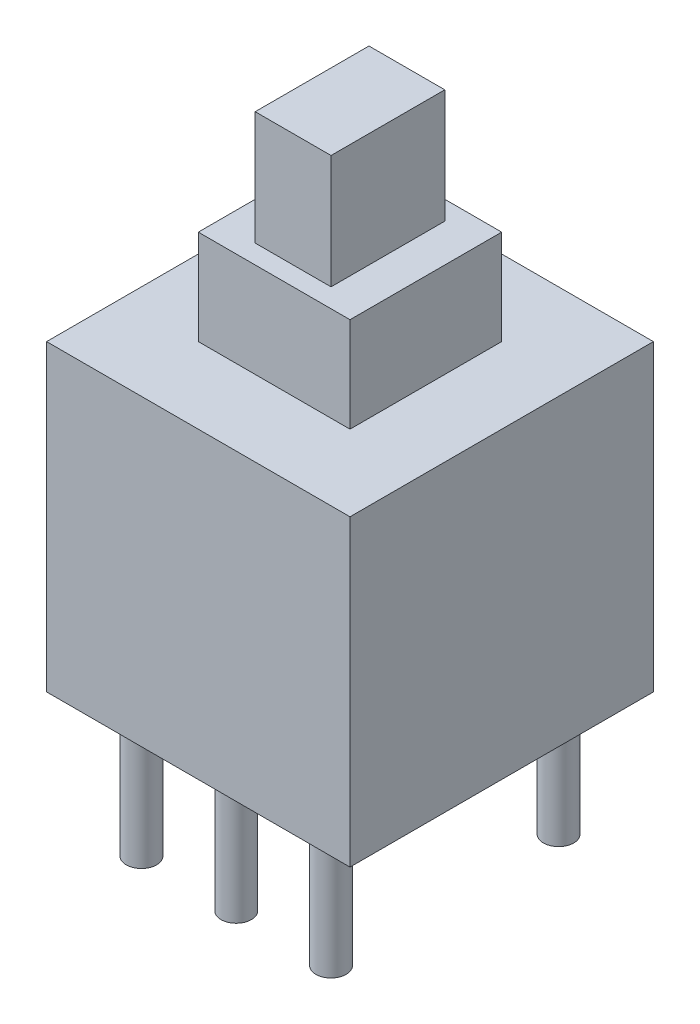
SolidWorks part; units mm, degrees
ref_plane "Front Plane" through (0, 0, 0) normal (0, 0, 1) x (1, 0, 0)
ref_plane "Top Plane" through (0, 0, 0) normal (0, 1, 0) x (1, 0, 0)
ref_plane "Right Plane" through (0, 0, 0) normal (1, 0, 0) x (0, 0, -1)
sketch "Sketch1" plane through (0, 0, 0) normal (0, 1, 0) x (1, 0, 0)
  line L0 (-4, 4) -> (4, -4) construction
  line L1 (-4, 4) -> (4, 4)
  line L2 (-4, 4) -> (-4, -4)
  line L3 (-4, -4) -> (4, -4)
  line L4 (4, 4) -> (4, -4)
  dimension "D1" = 8
extrude "Boss-Extrude1" add sketch "Sketch1" along normal blind 8
sketch "Sketch2" plane through (0, 8, 0) normal (0, 1, 0) x (1, 0, 0)
  line L5 (-2, -2) -> (2, -2)
  line L6 (-2, -2) -> (-2, 2)
  line L7 (-2, 2) -> (2, 2)
  line L8 (2, -2) -> (2, 2)
  line L9 (-2, -2) -> (2, 2) construction
  line L10 (-2, 2) -> (2, -2) construction
  point P4 (0, 0)
  dimension "D1" = 4
extrude "Boss-Extrude2" add sketch "Sketch2" along normal blind 5.5
sketch "Sketch3" plane through (0, 0, 0) normal (0, -1, 0) x (1, 0, 0)
  line L0 (0, -4.4) -> (0, 4.4) construction
  line L1 (-1.8601, 0) -> (1.942, 0) construction
  line L2 (4.4, 0) -> (-4.4, 0) construction
  line L3 (0, 3) -> (-2.5, 3) construction
  line L4 (0, 3) -> (2.5, 3) construction
  line L5 (0, -3) -> (2.5, -3) construction
  line L6 (0, -3) -> (-2.5, -3) construction
  circle A0 centre (0, 3) radius 0.4
  circle A2 centre (-2.5, 3) radius 0.4
  circle A3 centre (2.5, 3) radius 0.4
  circle A4 centre (2.5, -3) radius 0.4
  circle A5 centre (-2.5, -3) radius 0.4
  circle A6 centre (0, -3) radius 0.4
  dimension "D1" = 0.8
  dimension "D2" = 2.5
  dimension "D3" = 3
extrude "Boss-Extrude3" add sketch "Sketch3" along normal blind 3.5
sketch "Sketch4" plane through (0, 13.5, 0) normal (0, 1, 0) x (1, 0, 0)
  line L0 (-2, -2) -> (2, -2) construction
  line L1 (-2, 2) -> (-1, 2)
  line L2 (-2, 2) -> (-2, -2)
  line L3 (-2, -2) -> (-1, -2)
  line L4 (-1, 2) -> (-1, -2)
  line L5 (2, 2) -> (-2, 2) construction
  line L6 (2, -2) -> (1, -2)
  line L7 (2, -2) -> (2, 2)
  line L8 (2, 2) -> (1, 2)
  line L9 (1, -2) -> (1, 2)
  line L10 (1, 2) -> (-1, -2) construction
  dimension "D1" = 2
extrude "Cut-Extrude1" cut sketch "Sketch4" against normal blind 3
sketch "Sketch5" plane through (0, 0, 0) normal (1, 0, 0) x (0, 0, -1)
  line L0 (-1.5, 13.5) -> (-1.5, 10.5)
  line L1 (1.5, 13.5) -> (1.5, 10.5)
  line L2 (0, 4.4) -> (0, -4.4) construction
  line L3 (-1.5, 13.5) -> (-2, 13.5)
  line L4 (2, 13.5) -> (-2, 13.5)
  line L5 (-2, 13.5) -> (-2, 10.5)
  line L6 (-2, 10.5) -> (2, 10.5)
  line L7 (2, 10.5) -> (2, 13.5)
  line L8 (2, 13.5) -> (1.5, 13.5)
  line L9 (-2, 13.5) -> (-2, 10.5)
  line L10 (-2, 10.5) -> (-1.5, 10.5)
  line L11 (2, 10.5) -> (2, 13.5)
  line L12 (1.5, 10.5) -> (2, 10.5)
  dimension "D2" = 1.5
  dimension "D3" = 1.5
  dimension "D1" = 0
extrude "Cut-Extrude2" cut sketch "Sketch5" against normal through all both and the other way through all
